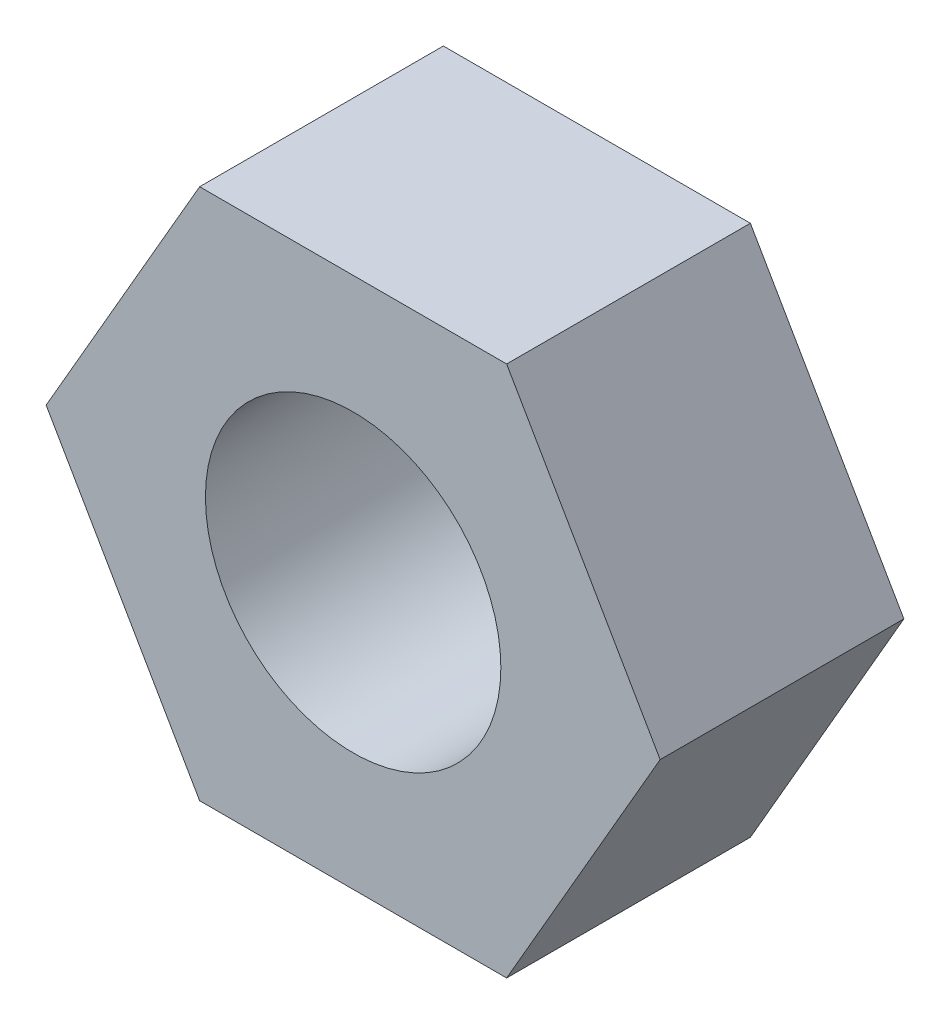
SolidWorks part; units mm, degrees
ref_plane "Front Plane" through (0, 0, 0) normal (0, 0, 1) x (1, 0, 0)
ref_plane "Top Plane" through (0, 0, 0) normal (0, 1, 0) x (1, 0, 0)
ref_plane "Right Plane" through (0, 0, 0) normal (1, 0, 0) x (0, 0, -1)
sketch "Sketch1" plane through (0, 0, 0) normal (0, 0, 1) x (1, 0, 0)
  line L1 (4.1569, 0) -> (2.0785, 3.6)
  line L2 (2.0785, 3.6) -> (-2.0785, 3.6)
  line L3 (-2.0785, 3.6) -> (-4.1569, 0)
  line L4 (-4.1569, 0) -> (-2.0785, -3.6)
  line L5 (-2.0785, -3.6) -> (2.0785, -3.6)
  line L6 (2.0785, -3.6) -> (4.1569, 0)
  circle A0 centre (0, 0) radius 3.6 construction
  circle A1 centre (0, 0) radius 2
  dimension "D2" = 4
  dimension "D1" = 7.2
extrude "Boss-Extrude1" add sketch "Sketch1" along normal blind 3.3
